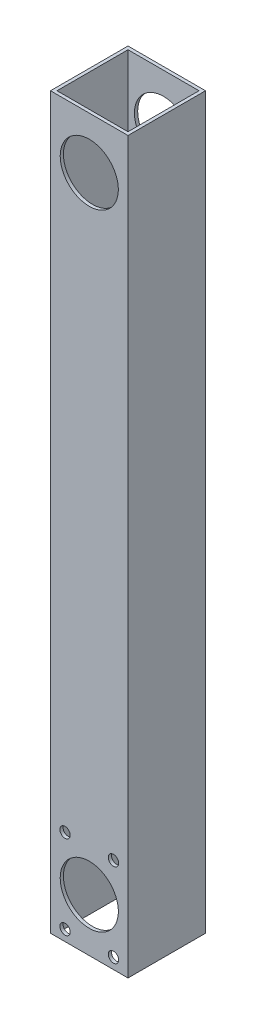
SolidWorks part; units mm, degrees
ref_plane "Front Plane" through (0, 0, 0) normal (0, 0, 1) x (1, 0, 0)
ref_plane "Top Plane" through (0, 0, 0) normal (0, 1, 0) x (1, 0, 0)
ref_plane "Right Plane" through (0, 0, 0) normal (1, 0, 0) x (0, 0, -1)
sketch "Sketch1" plane through (0, 0, 0) normal (0, 1, 0) x (1, 0, 0)
  line L1 (-17.4625, -17.4625) -> (17.4625, -17.4625)
  line L2 (-17.4625, -17.4625) -> (-17.4625, 17.4625)
  line L3 (-17.4625, 17.4625) -> (17.4625, 17.4625)
  line L4 (17.4625, -17.4625) -> (17.4625, 17.4625)
  line L5 (-17.4625, -17.4625) -> (17.4625, 17.4625) construction
  line L6 (-17.4625, 17.4625) -> (17.4625, -17.4625) construction
  line L7 (-19.05, -19.05) -> (19.05, -19.05)
  line L8 (-19.05, -19.05) -> (-19.05, 19.05)
  line L9 (-19.05, 19.05) -> (19.05, 19.05)
  line L10 (19.05, -19.05) -> (19.05, 19.05)
  line L11 (-19.05, -19.05) -> (19.05, 19.05) construction
  line L12 (-19.05, 19.05) -> (19.05, -19.05) construction
  point P0 (0, 0)
  point P5 (0, 0)
  dimension "D1" = 38.1
  dimension "D2" = 1.5875
extrude "Boss-Extrude1" add sketch "Sketch1" along normal blind 358.775
sketch "Sketch2" plane through (0, 0, -19.05) normal (0, 0, -1) x (-1, 0, 0)
  line L0 (0, 333.375) -> (0, 358.775) construction
  line L1 (-19.05, 358.775) -> (19.05, 358.775) construction
  line L2 (0, 333.375) -> (0, 25.9334) construction
  line L3 (-11.9062, 5.3112) -> (0, 25.9334) construction
  line L4 (-23.8125, 25.9334) -> (0, 25.9334) construction
  line L5 (-11.9063, 46.5556) -> (0, 25.9334) construction
  line L6 (11.9062, 46.5556) -> (0, 25.9334) construction
  line L7 (23.8125, 25.9334) -> (0, 25.9334) construction
  line L8 (11.9063, 5.3112) -> (0, 25.9334) construction
  circle A0 centre (0, 333.375) radius 14.2875
  circle A1 centre (0, 25.9334) radius 23.8125 construction
  circle A2 centre (-11.9062, 5.3112) radius 2.5527
  circle A3 centre (-23.8125, 25.9334) radius 2.5527 construction
  circle A4 centre (-11.9063, 46.5556) radius 2.5527
  circle A5 centre (11.9062, 46.5556) radius 2.5527
  circle A6 centre (23.8125, 25.9334) radius 2.5527 construction
  circle A7 centre (11.9063, 5.3112) radius 2.5527
  circle A8 centre (0, 25.9334) radius 14.2949
  point P23 (0, 25.9334)
  dimension "D1" = 28.575
  dimension "D7" = 6
  dimension "D4" = 47.625
  dimension "D5" = 150
  dimension "D6" = 5.1054
  dimension "D8" = 28.5898
  dimension "D2" = 25.4
  dimension "D3" = 307.4416
extrude "Cut-Extrude1" cut sketch "Sketch2" against normal through all
